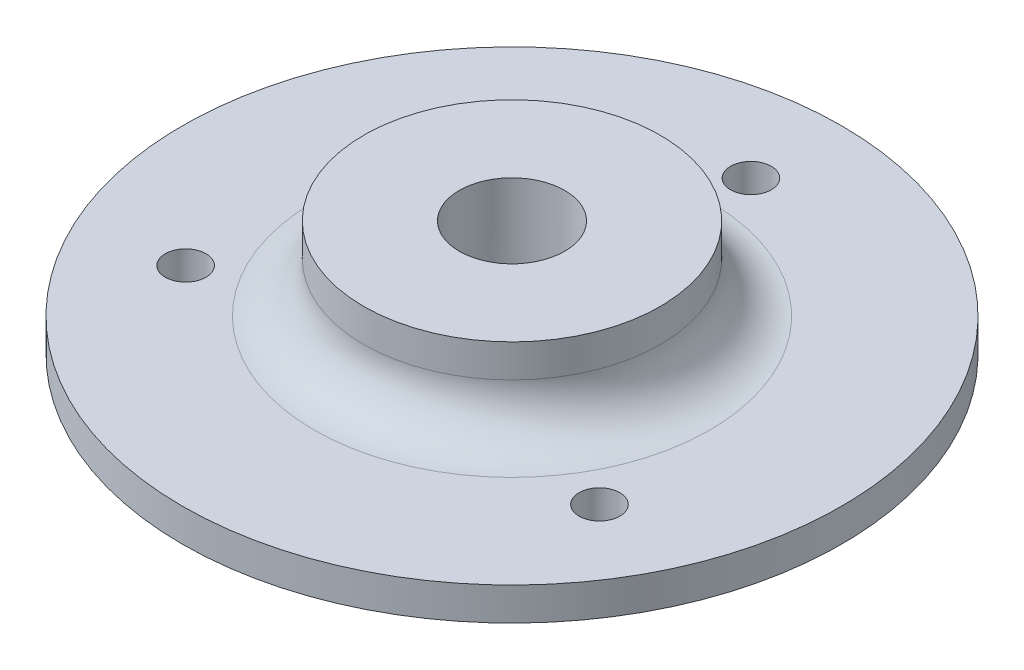
SolidWorks part; units mm, degrees
ref_plane "Front Plane" through (0, 0, 0) normal (0, 0, 1) x (1, 0, 0)
ref_plane "Top Plane" through (0, 0, 0) normal (0, 1, 0) x (1, 0, 0)
ref_plane "Right Plane" through (0, 0, 0) normal (1, 0, 0) x (0, 0, -1)
sketch "Sketch1" plane through (0, 0, 0) normal (1, 0, 0) x (0, 0, -1)
  line L0 (0, 0) -> (0, -5)
  line L1 (0, -5) -> (-11, -5)
  line L2 (-11, -5) -> (-11, -7)
  line L3 (-11, -7) -> (3.8, -7)
  line L4 (5.8, -5) -> (5.8, 0)
  line L5 (5.8, 0) -> (0, 0)
  line L6 (9, 1.6586) -> (9, -12.6289) construction
  line L7 (5.8, -5) -> (3.8, -7)
  point P6 (-11, -6)
  dimension "D1" = 20
  dimension "D2" = 3.2
  dimension "D3" = 45
  dimension "D4" = 9
  dimension "D5" = 2
  dimension "D7" = 7
revolve "Revolve1" add sketch "Sketch1" angle 360 about L6
sketch "Sketch2" plane through (0, -5, 0) normal (0, 1, 0) x (1, 0, 0)
  line L0 (0, 18) -> (0, 23.5) construction
  line L1 (0, 23.5) -> (0, 29) construction
  circle A0 centre (0, 23.5) radius 1.237
  circle A1 centre (0, 9) radius 9 construction
  circle A2 centre (0, 9) radius 14.5
  circle A3 centre (0, 9) radius 9 construction
  circle A4 centre (0, 9) radius 20 construction
  point P15 (0, 0)
  point P16 (0, 15.6869)
extrude "Cut-Extrude1" cut sketch "Sketch2" against normal through all contours A2 A0 | A0 A2
pattern_circular "CirPattern1" count 3 over 360 about axis through (0, 0, -9) along (0, 1, 0) of "Cut-Extrude1"
fillet "Fillet2" radius 3 1 edges at (0, -5, 0)
fillet "Fillet3" radius 1 1 edges at (0, -5, -5.8)
